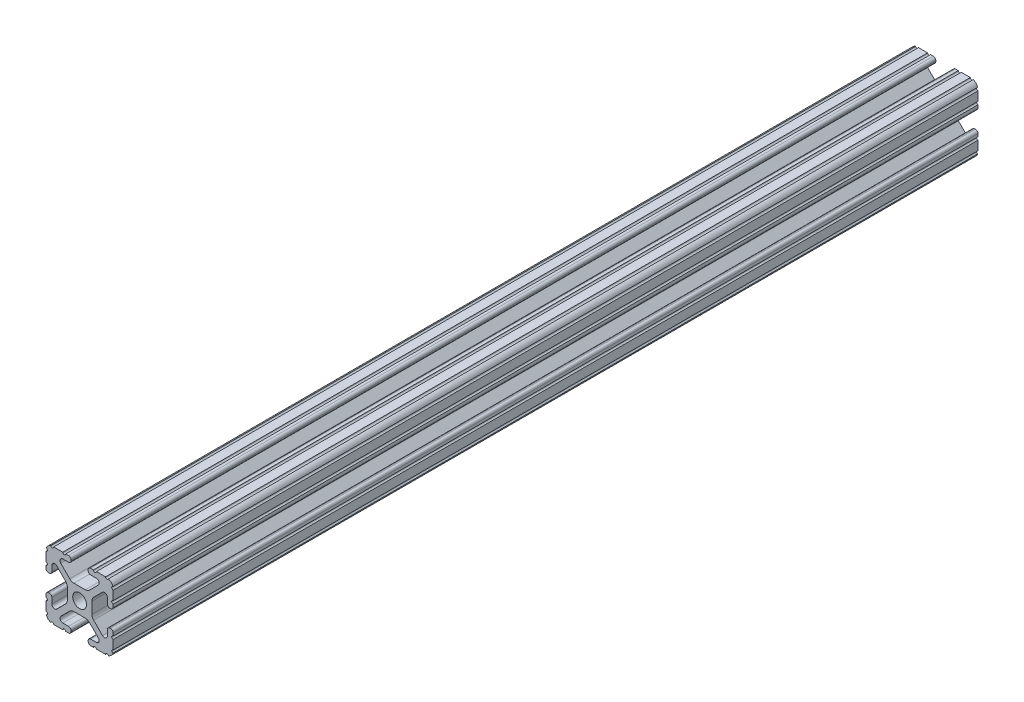
SolidWorks part; units mm, degrees
ref_plane "Front Plane" through (0, 0, 0) normal (0, 0, 1) x (1, 0, 0)
ref_plane "Top Plane" through (0, 0, 0) normal (0, 1, 0) x (1, 0, 0)
ref_plane "Right Plane" through (0, 0, 0) normal (1, 0, 0) x (0, 0, -1)
sketch "Sketch2" plane through (0, 0, 0) normal (0, 0, 1) x (1, 0, 0)
  line L0 (0, 12.7) -> (0, -12.7) construction
  line L1 (-12.7, 0) -> (12.7, 0) construction
  line L2 (3.2512, -12.7) -> (12.7, -12.7)
  line L3 (12.7, -12.7) -> (12.7, -3.2512)
  line L4 (3.2512, -12.7) -> (3.2512, -10.4902)
  line L5 (3.2512, -10.4902) -> (8.9276, -10.4902)
  line L6 (8.9276, -10.4902) -> (3.0856, -4.6482)
  line L7 (0, 0) -> (12.7, -12.7) construction
  line L8 (12.7, -3.2512) -> (10.4902, -3.2512)
  line L9 (10.4902, -3.2512) -> (10.4902, -8.9276)
  line L10 (10.4902, -8.9276) -> (4.6482, -3.0856)
  circle A0 centre (0, 0) radius 2.6035
  arc A1 (6.3485, -10.4902) -> (7.1039, -8.6665) centre (6.3485, -9.4219) ccw construction
  point P8 (0, -4.6482)
  dimension "Center Hole Diameter" = 5.207
  dimension "Rail Height" = 25.4
  dimension "Rail Width" = 25.4
  dimension "T-Slot Width" = 6.5024
  dimension "Slot Inner Width" = 14.8336
  dimension "Thickness" = 2.2098
  dimension "Slot Depth" = 5.842
  dimension "D1" = 2.2098
sketch "Sketch3" plane through (0, 0, 0) normal (1, 0, 0) x (0, 0, -1)
  line L0 (-163.5125, -12.7) -> (163.5125, -12.7) construction
  line L1 (-138.1125, 0) -> (138.1125, 0) construction
  line L3 (163.5125, 0) -> (-163.5125, 0) construction
sketch "Sketch4" plane through (0, 0, 0) normal (0, 0, 1) x (1, 0, 0)
  line L0 (4.1904, -12.7) -> (10.1173, -12.7)
  line L1 (3.2512, -12.7) -> (12.7, -12.7) construction
  line L2 (3.2512, -12.7) -> (3.2512, -10.4902) construction
  line L3 (3.2512, -10.4902) -> (8.9276, -10.4902) construction
  line L4 (3.2512, -11.4294) -> (3.2512, -11.7608)
  line L5 (4.1904, -10.4902) -> (6.3485, -10.4902)
  line L6 (0, -4.6482) -> (2.164, -4.6482)
  line L7 (8.9276, -10.4902) -> (3.0856, -4.6482) construction
  line L8 (3.7373, -5.2999) -> (7.1039, -8.6665)
  line L9 (12.7, -12.7) -> (12.7, -3.2512) construction
  line L10 (10.4902, -8.9276) -> (4.6482, -3.0856) construction
  line L11 (10.4902, -3.2512) -> (10.4902, -8.9276) construction
  line L12 (10.4902, -6.3485) -> (10.4902, -4.1904)
  line L13 (12.7, -3.2512) -> (10.4902, -3.2512) construction
  line L14 (11.4294, -3.2512) -> (11.7608, -3.2512)
  line L15 (12.7, -4.1904) -> (12.7, -10.1173)
  line L16 (8.6665, -7.1039) -> (5.2999, -3.7373)
  line L17 (4.6482, 0) -> (4.6482, -2.164)
  line L18 (-12.7, 0) -> (12.7, 0) construction
  line L19 (0, -4.6482) -> (0, -2.6035)
  line L20 (0, 12.7) -> (0, -12.7) construction
  line L21 (4.6482, 0) -> (2.6035, 0)
  arc A0 (3.2512, -11.7608) -> (4.1904, -12.7) centre (4.1904, -11.7608) ccw
  arc A2 (3.2512, -11.4294) -> (4.1904, -10.4902) centre (4.1904, -11.4294) cw
  arc A3 (6.3485, -10.4902) -> (7.1039, -8.6665) centre (6.3485, -9.4219) ccw
  arc A4 (2.164, -4.6482) -> (3.7373, -5.2999) centre (2.164, -6.8732) cw
  arc A5 (10.1173, -12.7) -> (12.7, -10.1173) centre (10.1173, -10.1173) ccw
  arc A6 (8.6665, -7.1039) -> (10.4902, -6.3485) centre (9.4219, -6.3485) ccw
  arc A7 (10.4902, -4.1904) -> (11.4294, -3.2512) centre (11.4294, -4.1904) cw
  arc A8 (11.7608, -3.2512) -> (12.7, -4.1904) centre (11.7608, -4.1904) cw
  arc A9 (5.2999, -3.7373) -> (4.6482, -2.164) centre (6.8732, -2.164) cw
  circle A10 centre (0, 0) radius 2.6035 construction
  arc A11 (0, -2.6035) -> (2.6035, 0) centre (0, 0) ccw
  dimension "D1" = 2.5827
  dimension "D2" = 2.225
  dimension "D3" = 0.9392
extrude "Boss-Extrude1" add sketch "Sketch4" along normal up to vertex (163.5125 mm away) from vertex at -163.5125 starting at point (0, -12.7, -163.5125)
sketch "Sketch5" plane through (0, 0, 0) normal (0, 0, 1) x (1, 0, 0)
  line L0 (3.2512, -12.7) -> (12.7, -12.7) construction
  line L1 (4.1904, -10.4902) -> (6.3485, -10.4902) construction
  line L3 (0, 0) -> (12.7, -12.7) construction
  line L4 (6.3485, -10.4902) -> (6.3485, -12.7) construction
  line L5 (8.9276, -10.4902) -> (3.0856, -4.6482) construction
  circle A0 centre (10.3562, -12.7) radius 0.5524
  circle A1 centre (5.796, -12.7) radius 0.5524
  circle A2 centre (12.7, -10.3562) radius 0.5524
  circle A3 centre (12.7, -5.796) radius 0.5524
  point P10 (5.2694, -10.4902)
  point P12 (9.4219, -6.3485)
  dimension "D1" = 1.1049
extrude "Cut-Extrude1" cut sketch "Sketch5" against normal through all both and the other way through all
mirror "Mirror1" about plane through (0, 0, 0) normal (1, 0, 0) of bodies 137 134
mirror "Mirror2" about plane through (0, 0, 0) normal (0, 1, 0) of bodies 135
equation "\"D1@Sketch2\"=\"Thickness@Sketch2\""
equation "\"D2@Sketch4\"=\"Slot Inner Width@Sketch2\"*0.15"
equation "\"D1@Sketch4\"=\"D3@Sketch4\"*2.75"
equation "\"D3@Sketch4\"=\"Thickness@Sketch2\"*0.425"
equation "\"D1@Sketch5\"=\"Thickness@Sketch2\"*0.5"
equation "\"D1@Boss-Extrude1\"=\"Length@Sketch3\""
